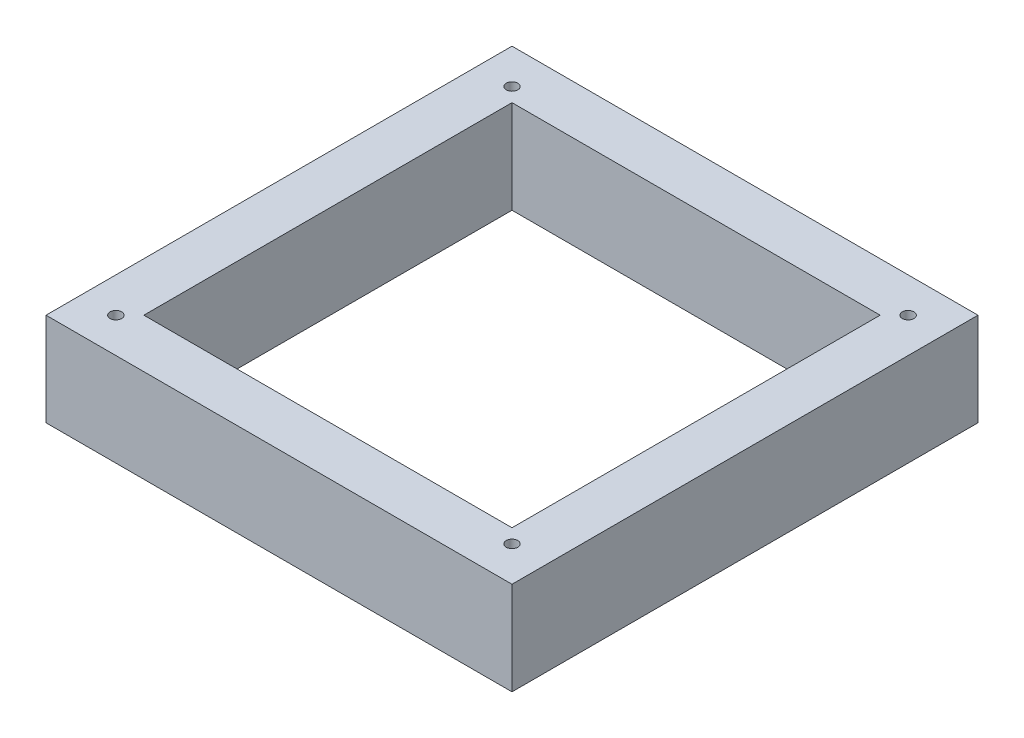
SolidWorks part; units mm, degrees
ref_plane "Alzado" through (0, 0, 0) normal (0, 0, 1) x (1, 0, 0)
ref_plane "Planta" through (0, 0, 0) normal (0, 1, 0) x (1, 0, 0)
ref_plane "Vista lateral" through (0, 0, 0) normal (1, 0, 0) x (0, 0, -1)
sketch "Croquis1" plane through (0, 0, 0) normal (0, 1, 0) x (1, 0, 0)
  line L0 (0, 0) -> (200, 200) construction
  line L1 (0, 0) -> (200, 0)
  line L2 (0, 0) -> (0, 200)
  line L3 (0, 200) -> (200, 200)
  line L4 (200, 0) -> (200, 200)
  line L6 (21, 21) -> (179, 21)
  line L7 (21, 21) -> (21, 179)
  line L8 (21, 179) -> (179, 179)
  line L9 (179, 21) -> (179, 179)
  line L10 (21, 21) -> (179, 179) construction
  line L11 (21, 179) -> (179, 21) construction
  line L12 (15, 15) -> (185, 15) construction
  line L13 (15, 15) -> (15, 185) construction
  line L14 (15, 185) -> (185, 185) construction
  line L15 (185, 15) -> (185, 185) construction
  line L16 (15, 15) -> (185, 185) construction
  line L17 (15, 185) -> (185, 15) construction
  circle A0 centre (185, 185) radius 2.5
  circle A1 centre (185, 15) radius 2.5
  circle A2 centre (15, 15) radius 2.5
  circle A3 centre (15, 185) radius 2.5
  point P4 (100, 100)
  point P10 (100, 100)
  dimension "D4" = 5
  dimension "D1" = 200
  dimension "D2" = 158
  dimension "D3" = 170
extrude "Saliente-Extruir1" add sketch "Croquis1" along normal blind 40
